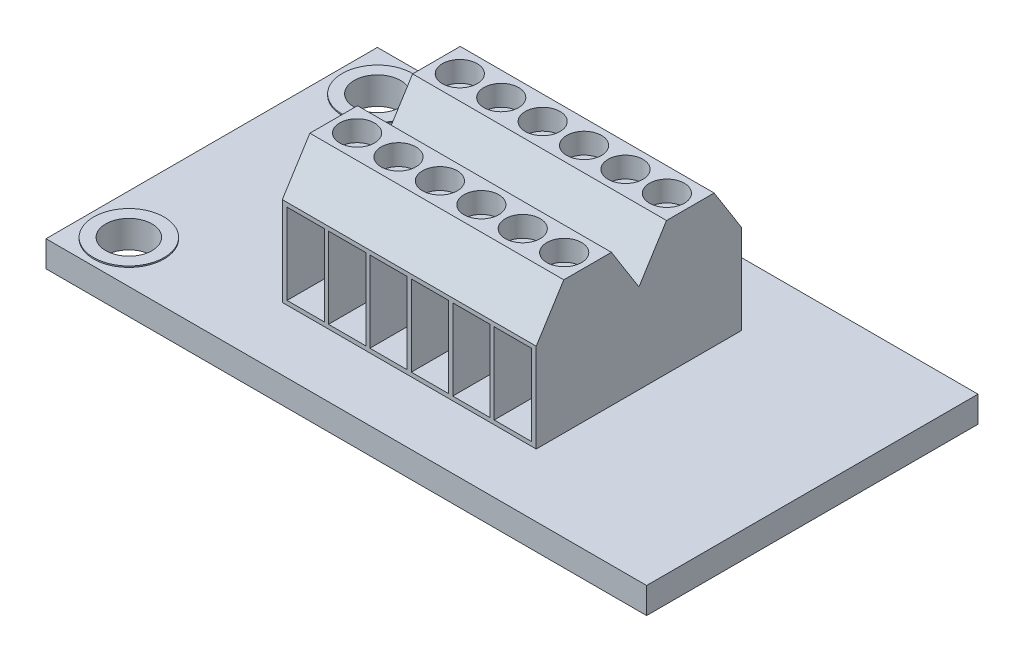
SolidWorks part; units mm, degrees
ref_plane "Front Plane" through (0, 0, 0) normal (0, 0, 1) x (1, 0, 0)
ref_plane "Top Plane" through (0, 0, 0) normal (0, 1, 0) x (1, 0, 0)
ref_plane "Right Plane" through (0, 0, 0) normal (1, 0, 0) x (0, 0, -1)
sketch "Sketch1" plane through (0, 0, 0) normal (0, 1, 0) x (1, 0, 0)
  line L1 (-18.415, 10.16) -> (18.415, 10.16)
  line L2 (-18.415, 10.16) -> (-18.415, -10.16)
  line L3 (-18.415, -10.16) -> (18.415, -10.16)
  line L4 (18.415, 10.16) -> (18.415, -10.16)
  line L5 (-18.415, 10.16) -> (18.415, -10.16) construction
  line L6 (-18.415, -10.16) -> (18.415, 10.16) construction
  point P0 (0, 0)
  dimension "D1" = 20.32
  dimension "D2" = 36.83
extrude "Boss-Extrude1" add sketch "Sketch1" along normal blind 1.6002 contours L1 L4 L3 L2
sketch "Sketch5" plane through (0, 0, 0) normal (0, 1, 0) x (1, 0, 0)
  line L0 (-18.415, 10.16) -> (-18.415, -10.16) construction
  line L2 (-18.415, -10.16) -> (18.415, -10.16) construction
  circle A0 centre (-15.875, 7.62) radius 1.4224
  circle A1 centre (-15.875, -7.62) radius 1.4224
  dimension "D1" = 2.54
  dimension "D2" = 2.54
  dimension "D4" = 2.54
  dimension "D5" = 2.8448
  dimension "D3" = 15.24
extrude "Cut-Extrude3" cut sketch "Sketch5" along normal through all contours A1 | A0
sketch "Sketch8" plane through (0, 0, 0) normal (1, 0, 0) x (0, 0, -1)
  line L0 (0, 1.6002) -> (6.2992, 1.6002)
  line L1 (10.16, 1.6002) -> (-10.16, 1.6002) construction
  line L2 (0, 1.6002) -> (0, 7.0612)
  line L3 (6.2992, 1.6002) -> (6.2992, 7.0612)
  line L4 (1.6891, 9.7428) -> (4.6101, 9.7428)
  line L5 (0, 7.0612) -> (1.6891, 9.7428)
  line L6 (4.6101, 9.7428) -> (6.2992, 7.0612)
  point P5 (0.2743, 1.6002)
  point P6 (0, 0)
  point P10 (0, 0)
  point P11 (0, 0)
  point P12 (0, 0)
  point P13 (0, 0)
  point P14 (0, 0)
  dimension "D1" = 0
  dimension "D2" = 2.921
  dimension "D3" = 6.2992
  dimension "D5" = 2.6816
extrude "Boss-Extrude2" add sketch "Sketch8" along normal mid plane 15.5702
sketch "Sketch10" plane through (0, 0, 0) normal (1, 0, 0) x (0, 0, -1)
  line L0 (-6.2992, 1.6002) -> (0, 1.6002)
  line L1 (-6.2992, 1.6002) -> (-6.2992, 7.0612)
  line L2 (0, 1.6002) -> (0, 7.0612)
  line L3 (-4.6101, 9.7428) -> (-1.6891, 9.7428)
  line L4 (-6.2992, 7.0612) -> (-4.6101, 9.7428)
  line L5 (-1.6891, 9.7428) -> (0, 7.0612)
  line L6 (10.16, 1.6002) -> (-10.16, 1.6002) construction
  point P3 (-3.1496, -4.0713)
  point P7 (0, 0)
  dimension "D1" = 0
  dimension "D2" = 0
extrude "Boss-Extrude3" add sketch "Sketch10" along normal mid plane 15.5702
sketch "Sketch11" plane through (0, 0, 6.2992) normal (0, 0, 1) x (1, 0, 0)
  line L0 (7.7851, 4.3307) -> (-7.7851, 4.3307) construction
  line L1 (-2.413, 1.8542) -> (-0.127, 1.8542)
  line L2 (-2.413, 1.8542) -> (-2.413, 6.8072)
  line L3 (-2.413, 6.8072) -> (-0.127, 6.8072)
  line L4 (-0.127, 1.8542) -> (-0.127, 6.8072)
  line L5 (-2.413, 1.8542) -> (-0.127, 6.8072) construction
  line L6 (-2.413, 6.8072) -> (-0.127, 1.8542) construction
  line L7 (7.7851, 7.0612) -> (7.7851, 1.6002) construction
  line L8 (-7.7851, 7.0612) -> (-7.7851, 1.6002) construction
  line L9 (0, 1.6002) -> (0, 7.9155) construction
  line L10 (-18.415, 1.6002) -> (18.415, 1.6002) construction
  line L11 (7.7851, 7.0612) -> (-7.7851, 7.0612) construction
  line L12 (-4.953, 1.8542) -> (-4.953, 6.8072)
  line L13 (-4.953, 1.8542) -> (-2.667, 1.8542)
  line L14 (-2.667, 1.8542) -> (-2.667, 6.8072)
  line L15 (-4.953, 6.8072) -> (-2.667, 6.8072)
  line L16 (-7.493, 1.8542) -> (-7.493, 6.8072)
  line L17 (-7.493, 1.8542) -> (-5.207, 1.8542)
  line L18 (-5.207, 1.8542) -> (-5.207, 6.8072)
  line L19 (-7.493, 6.8072) -> (-5.207, 6.8072)
  line L20 (-2.413, 1.8542) -> (-4.953, 1.8542) construction
  line L21 (0.127, 1.8542) -> (2.413, 1.8542)
  line L22 (0.127, 1.8542) -> (0.127, 6.8072)
  line L23 (0.127, 6.8072) -> (2.413, 6.8072)
  line L24 (2.413, 1.8542) -> (2.413, 6.8072)
  line L25 (7.7851, 1.6002) -> (-7.7851, 1.6002) construction
  line L26 (2.667, 1.8542) -> (4.953, 1.8542)
  line L27 (4.953, 1.8542) -> (4.953, 6.8072)
  line L28 (2.667, 6.8072) -> (4.953, 6.8072)
  line L29 (2.667, 1.8542) -> (2.667, 6.8072)
  line L30 (5.207, 1.8542) -> (7.493, 1.8542)
  line L31 (7.493, 1.8542) -> (7.493, 6.8072)
  line L32 (5.207, 6.8072) -> (7.493, 6.8072)
  line L33 (5.207, 1.8542) -> (5.207, 6.8072)
  line L34 (0.127, 1.8542) -> (2.667, 1.8542) construction
  point P0 (-1.27, 4.3307)
  dimension "D1" = 2.286
  dimension "D2" = 0.254
  dimension "D3" = 0.127
  dimension "D5" = 2.54
  dimension "D6" = 0.127
  dimension "D7" = 0.254
  dimension "D8" = 0.254
  dimension "D9" = 2.286
  dimension "D11" = 2.54
  dimension "D4" = 3
  dimension "D10" = 3
extrude "Cut-Extrude5" cut sketch "Sketch11" against normal blind 2.54
sketch "Sketch12" plane through (0, 0, -6.2992) normal (0, 0, -1) x (-1, 0, 0)
  line L0 (-7.7851, 7.0612) -> (7.7851, 7.0612) construction
  line L1 (-2.413, 1.8542) -> (-0.127, 1.8542)
  line L2 (-2.413, 1.8542) -> (-2.413, 6.8072)
  line L3 (-2.413, 6.8072) -> (-0.127, 6.8072)
  line L4 (-0.127, 1.8542) -> (-0.127, 6.8072)
  line L5 (-2.413, 1.8542) -> (-0.127, 6.8072) construction
  line L6 (-2.413, 6.8072) -> (-0.127, 1.8542) construction
  line L7 (-7.7851, 1.6002) -> (7.7851, 1.6002) construction
  line L9 (0, 0.5578) -> (0, -0.5578) construction
  line L12 (-4.953, 1.8542) -> (-4.953, 6.8072)
  line L13 (-4.953, 1.8542) -> (-2.667, 1.8542)
  line L14 (-2.667, 1.8542) -> (-2.667, 6.8072)
  line L15 (-4.953, 6.8072) -> (-2.667, 6.8072)
  line L16 (-7.493, 1.8542) -> (-7.493, 6.8072)
  line L17 (-7.493, 1.8542) -> (-5.207, 1.8542)
  line L18 (-5.207, 1.8542) -> (-5.207, 6.8072)
  line L19 (-7.493, 6.8072) -> (-5.207, 6.8072)
  line L20 (-2.413, 1.8542) -> (-4.953, 1.8542) construction
  line L21 (0.127, 1.8542) -> (2.413, 1.8542)
  line L22 (0.127, 1.8542) -> (0.127, 6.8072)
  line L23 (0.127, 6.8072) -> (2.413, 6.8072)
  line L24 (2.413, 1.8542) -> (2.413, 6.8072)
  line L26 (2.667, 1.8542) -> (4.953, 1.8542)
  line L27 (4.953, 1.8542) -> (4.953, 6.8072)
  line L28 (2.667, 6.8072) -> (4.953, 6.8072)
  line L29 (2.667, 1.8542) -> (2.667, 6.8072)
  line L30 (5.207, 1.8542) -> (7.493, 1.8542)
  line L31 (7.493, 1.8542) -> (7.493, 6.8072)
  line L32 (5.207, 6.8072) -> (7.493, 6.8072)
  line L33 (5.207, 1.8542) -> (5.207, 6.8072)
  line L34 (0.127, 1.8542) -> (2.667, 1.8542) construction
  point P0 (-1.27, 4.3307)
  dimension "D1" = 2.286
  dimension "D2" = 0.254
  dimension "D3" = 0.127
  dimension "D5" = 2.54
  dimension "D6" = 0.127
  dimension "D7" = 0.254
  dimension "D8" = 0.254
  dimension "D9" = 2.286
  dimension "D11" = 2.54
  dimension "D12" = 0.254
  dimension "D4" = 3
  dimension "D10" = 3
extrude "Cut-Extrude6" cut sketch "Sketch12" against normal blind 2.54
sketch "Sketch13" plane through (0, 9.7428, 0) normal (0, 1, 0) x (1, 0, 0)
  line L0 (-7.7851, -3.1496) -> (7.7851, -3.1496) construction
  line L1 (-7.7851, -1.6891) -> (-7.7851, -4.6101) construction
  line L2 (7.7851, -1.6891) -> (7.7851, -4.6101) construction
  line L3 (0, -1.6891) -> (0, -4.6101) construction
  line L4 (7.7851, -1.6891) -> (-7.7851, -1.6891) construction
  line L5 (7.7851, -4.6101) -> (-7.7851, -4.6101) construction
  line L6 (-1.27, -3.1496) -> (-3.81, -3.1496) construction
  line L7 (1.27, -3.1496) -> (3.81, -3.1496) construction
  circle A0 centre (-1.27, -3.1496) radius 1.0668
  circle A1 centre (-3.81, -3.1496) radius 1.0668
  circle A2 centre (-6.35, -3.1496) radius 1.0668
  circle A3 centre (1.27, -3.1496) radius 1.0668
  circle A4 centre (3.81, -3.1496) radius 1.0668
  circle A5 centre (6.35, -3.1496) radius 1.0668
  dimension "D1" = 2.1336
  dimension "D2" = 1.27
  dimension "D6" = 2.1336
  dimension "D3" = 2.54
  dimension "D5" = 1.27
  dimension "D7" = 2.54
  dimension "D4" = 3
extrude "Cut-Extrude7" cut sketch "Sketch13" against normal blind 1.27
sketch "Sketch17" plane through (0, 9.7428, 0) normal (0, 1, 0) x (1, 0, 0)
  line L0 (-7.7851, 3.1496) -> (7.7851, 3.1496) construction
  line L1 (-7.7851, 4.6101) -> (-7.7851, 1.6891) construction
  line L2 (7.7851, 4.6101) -> (7.7851, 1.6891) construction
  line L3 (0, 4.6101) -> (0, 1.6891) construction
  line L4 (7.7851, 4.6101) -> (-7.7851, 4.6101) construction
  line L5 (7.7851, 1.6891) -> (-7.7851, 1.6891) construction
  line L6 (-1.27, 3.1496) -> (-3.81, 3.1496) construction
  line L7 (1.27, 3.1496) -> (3.81, 3.1496) construction
  circle A0 centre (-1.27, 3.1496) radius 1.0668
  circle A1 centre (-3.81, 3.1496) radius 1.0668
  circle A2 centre (-6.35, 3.1496) radius 1.0668
  circle A3 centre (1.27, 3.1496) radius 1.0668
  circle A4 centre (3.81, 3.1496) radius 1.0668
  circle A5 centre (6.35, 3.1496) radius 1.0668
  dimension "D1" = 1.27
  dimension "D2" = 2.1336
  dimension "D5" = 1.27
  dimension "D6" = 2.1336
  dimension "D3" = 2.54
  dimension "D7" = 2.54
  dimension "D4" = 3
extrude "Cut-Extrude9" cut sketch "Sketch17" against normal blind 1.27
sketch "Sketch21" plane through (0, 1.6002, 0) normal (0, 1, 0) x (1, 0, 0)
  circle A0 centre (-15.875, -7.62) radius 2.159
  circle A1 centre (-15.875, -7.62) radius 1.4224
  circle A2 centre (-15.875, 7.62) radius 1.4224
  circle A3 centre (-15.875, 7.62) radius 2.159
  dimension "D1" = 4.318
  dimension "D2" = 4.318
  dimension "D3" = 2.8448
  dimension "D4" = 2.8448
extrude "Boss-Extrude5" add sketch "Sketch21" along normal blind 0.0762
